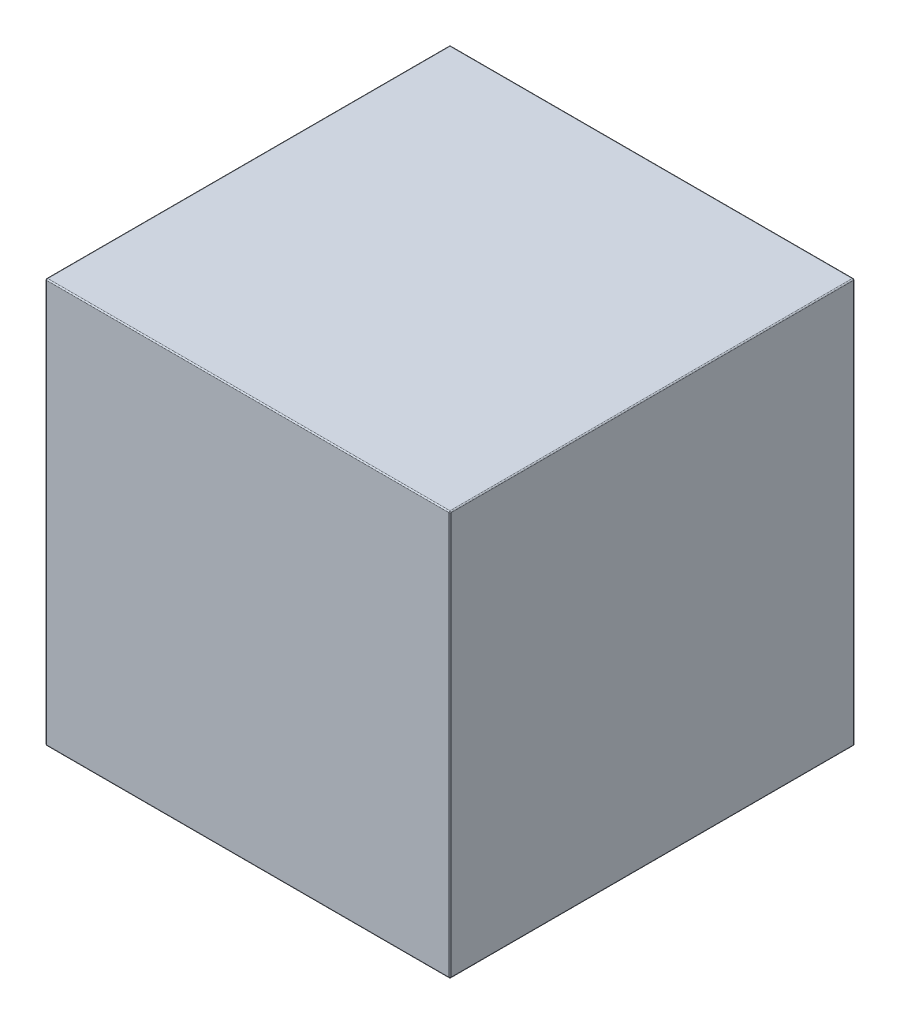
SolidWorks part; units mm, degrees
material "ESUN PLA +"
ref_plane "Front Plane" through (0, 0, 0) normal (0, 0, 1) x (1, 0, 0)
ref_plane "Top Plane" through (0, 0, 0) normal (0, 1, 0) x (1, 0, 0)
ref_plane "Right Plane" through (0, 0, 0) normal (1, 0, 0) x (0, 0, -1)
sketch "Sketch1" plane through (0, 0, 0) normal (0, 1, 0) x (1, 0, 0)
  line L1 (-175, 175) -> (175, 175)
  line L2 (-175, 175) -> (-175, -175)
  line L3 (-175, -175) -> (175, -175)
  line L4 (175, 175) -> (175, -175)
  line L5 (-175, 175) -> (175, -175) construction
  line L6 (-175, -175) -> (175, 175) construction
  point P0 (0, 0)
  dimension "D1" = 350
  dimension "D2" = 350
extrude "Boss-Extrude1" add sketch "Sketch1" along normal mid plane 350
fillet "Fillet1" radius 1 11 edges at (175, 0, -175) (-175, 0, -175) (0, 175, 175) (-175, 175, 0) (0, 175, -175) (175, 175, 0) (-175, 0, 175) (175, 0, 175) (0, -175, 175) (-175, -175, 0) (175, -175, 0)
